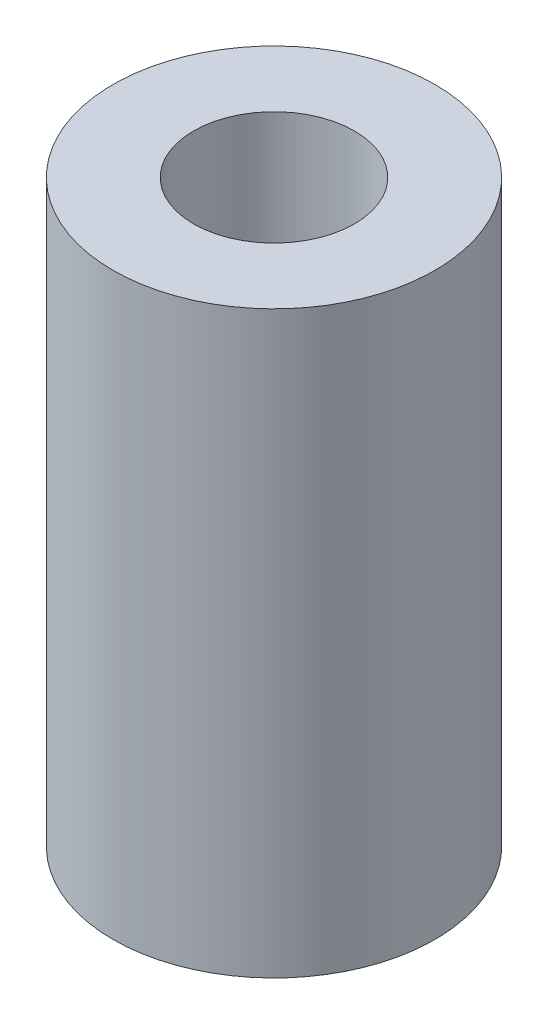
SolidWorks part; units mm, degrees
ref_plane "Спереди" through (0, 0, 0) normal (0, 0, 1) x (1, 0, 0)
ref_plane "Сверху" through (0, 0, 0) normal (0, 1, 0) x (1, 0, 0)
ref_plane "Справа" through (0, 0, 0) normal (1, 0, 0) x (0, 0, -1)
sketch "Эскиз1" plane through (0, 0, 0) normal (0, 1, 0) x (1, 0, 0)
  circle A0 centre (0, 0) radius 3.5
  circle A1 centre (0, 0) radius 7
extrude "Вытянуть1" add sketch "Эскиз1" along normal blind 25.2
